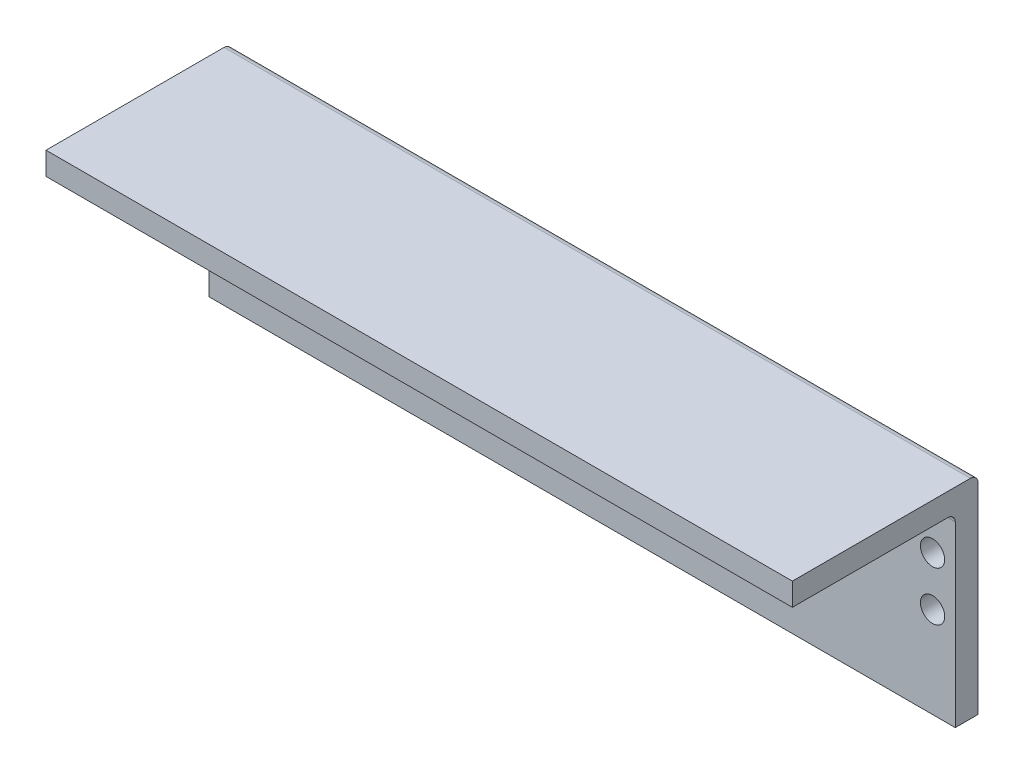
SolidWorks part; units mm, degrees
material "ABS"
ref_plane "前视基准面" through (0, 0, 0) normal (0, 0, 1) x (1, 0, 0)
ref_plane "上视基准面" through (0, 0, 0) normal (0, 1, 0) x (1, 0, 0)
ref_plane "右视基准面" through (0, 0, 0) normal (1, 0, 0) x (0, 0, -1)
other "Configuration Table"
sketch "草图1" plane through (0, 0, 0) normal (0, 0, 1) x (1, 0, 0)
  line L0 (-38.6665, 0) -> (31.2744, 0) construction
  line L1 (0, 22.4607) -> (0, -30.1372) construction
  line L2 (-49.25, 0) -> (49.25, 0)
  line L3 (-49.25, 0) -> (-49.25, 18.5)
  line L4 (-49.25, 18.5) -> (49.25, 18.5)
  line L5 (49.25, 0) -> (49.25, 18.5)
  circle A0 centre (-46.25, 3) radius 1.6
  circle A1 centre (-46.25, 9.5) radius 1.6
  circle A2 centre (46.25, 3) radius 1.6
  circle A3 centre (46.25, 9.5) radius 1.6
  dimension "D5" = 6.5
  dimension "D6" = 3.2
  dimension "D1" = 3
  dimension "D2" = 18.5
  dimension "D3" = 98.5
  dimension "D4" = 3
extrude "凸台-拉伸1" add sketch "草图1" along normal blind 3
sketch "草图2" plane through (0, 18.5, 0) normal (0, 1, 0) x (1, 0, 0)
  line L0 (49.25, -3) -> (49.25, 0) construction
  line L1 (-49.25, -3) -> (49.25, -3)
  line L2 (-49.25, -3) -> (-49.25, -24.5)
  line L3 (-49.25, -24.5) -> (49.25, -24.5)
  line L4 (49.25, -3) -> (49.25, -24.5)
  dimension "D1" = 21.5
extrude "凸台-拉伸2" add sketch "草图2" against normal blind 3
fillet "圆角1" radius 1 2 edges at (0, 15.5, 3) (0, 18.5, 0)
sketch "草图3" plane through (0, 0, 0) normal (0, -1, 0) x (1, 0, 0)
  line L4 (-49.25, 0) -> (49.25, 0)
  line L5 (49.25, 0) -> (49.25, 3)
  line L6 (49.25, 3) -> (-49.25, 3)
  line L7 (-49.25, 3) -> (-49.25, 0)
  line L8 (-49.25, 0) -> (49.25, 0)
  line L9 (49.25, 0) -> (49.25, 3)
  line L10 (49.25, 3) -> (-49.25, 3)
  line L11 (-49.25, 3) -> (-49.25, 0)
  dimension "D1" = 0
extrude "凸台-拉伸3" add sketch "草图3" along normal blind 9
